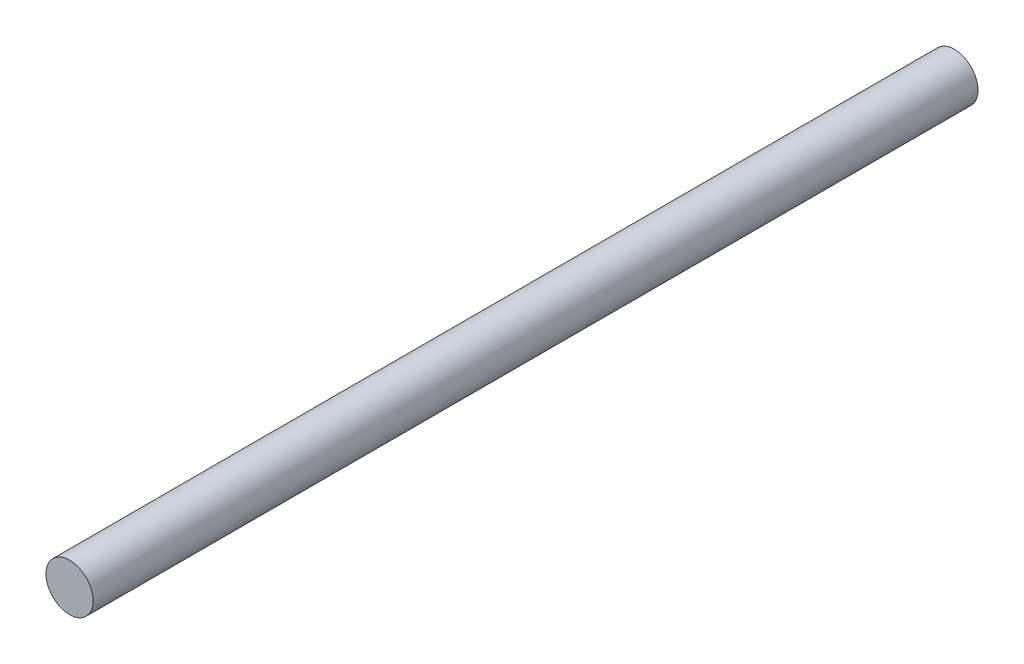
SolidWorks part; units mm, degrees
ref_plane "Front Plane" through (0, 0, 0) normal (0, 0, 1) x (1, 0, 0)
ref_plane "Top Plane" through (0, 0, 0) normal (0, 1, 0) x (1, 0, 0)
ref_plane "Right Plane" through (0, 0, 0) normal (1, 0, 0) x (0, 0, -1)
sketch "Sketch1" plane through (0, 0, 0) normal (0, 0, 1) x (1, 0, 0)
  circle A0 centre (0, 0) radius 4
extrude "Boss-Extrude1" add sketch "Sketch1" along normal blind 150
